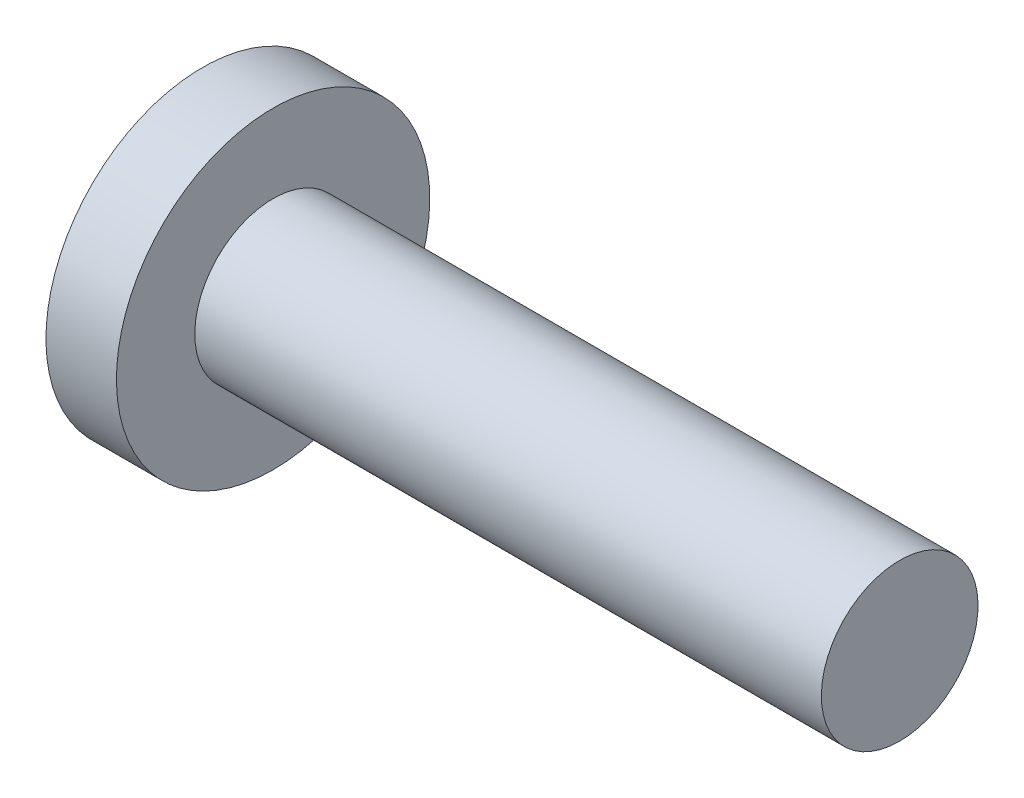
SolidWorks part; units mm, degrees
ref_plane "前视基准面" through (0, 0, 0) normal (0, 0, 1) x (1, 0, 0)
ref_plane "上视基准面" through (0, 0, 0) normal (0, 1, 0) x (1, 0, 0)
ref_plane "右视基准面" through (0, 0, 0) normal (1, 0, 0) x (0, 0, -1)
other "Configuration Table"
sketch "草图1" plane through (0, 0, 0) normal (0, 0, 1) x (1, 0, 0)
  line L0 (0, 0) -> (8, 0)
  line L1 (0, 0) -> (0, 1)
  line L2 (0, 1) -> (-0.9, 1)
  line L3 (8, 0) -> (8, -1)
  line L4 (6, -1) -> (4.7823, -1) construction
  line L5 (-0.9, 1) -> (-0.9, -1)
  line L6 (-0.9, -1) -> (8, -1)
  dimension "D1" = 8
  dimension "D3" = 0.9
  dimension "D4" = 1
  dimension "D5" = 2
revolve "旋转1" add sketch "草图1" angle 360 about L6
